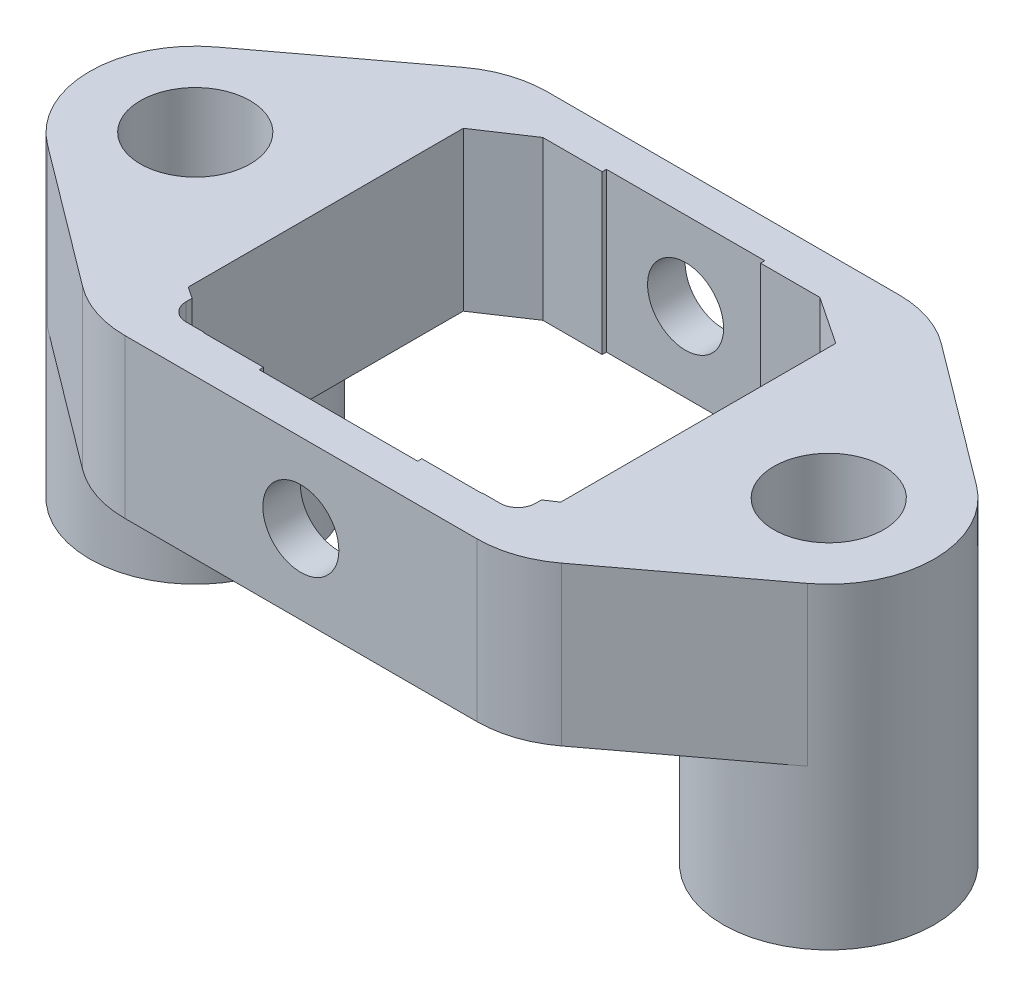
SolidWorks part; units mm, degrees
ref_plane "Front Plane" through (0, 0, 0) normal (0, 0, 1) x (1, 0, 0)
ref_plane "Top Plane" through (0, 0, 0) normal (0, 1, 0) x (1, 0, 0)
ref_plane "Right Plane" through (0, 0, 0) normal (1, 0, 0) x (0, 0, -1)
sketch "Sketch1" plane through (0, 0, 0) normal (0, 1, 0) x (1, 0, 0)
  line L0 (4.7625, -10.1854) -> (8.3298, -10.1854)
  line L5 (-4.7625, 10.1854) -> (-4.7625, 10.4394)
  line L6 (-12.7, -12.7) -> (12.7, -12.7)
  line L7 (4.7625, 10.1854) -> (8.3298, 10.1854)
  line L8 (-8.3298, 10.1854) -> (-11.2014, 8.271)
  line L9 (-8, 10.1) -> (-11, 8.1) construction
  line L10 (0, 0) -> (-11.2014, 0) construction
  line L11 (0, 0) -> (0, 10.4394) construction
  line L12 (-8.3298, -10.1854) -> (-8.3769, -10.154)
  line L13 (8.3298, -10.1854) -> (8.3769, -10.154)
  line L14 (8.3298, 10.1854) -> (11.2014, 8.271)
  line L15 (-8.3298, 10.1854) -> (-4.7625, 10.1854)
  line L34 (-10.504, -8.7359) -> (-11.2014, -8.271)
  line L35 (8.3769, -10.154) -> (9.4165, -10.154)
  line L36 (9.5863, -10.1409) -> (9.6154, -10.1409)
  line L37 (-9.5863, -10.1409) -> (-9.6154, -10.1409)
  line L38 (-8.75, -10.154) -> (-9.4165, -10.154)
  line L39 (-10.504, -9.1) -> (-10.504, -8.9)
  line L40 (-9.5863, -10.1409) -> (-9.6154, -10.1409)
  line L41 (-8.3769, -10.154) -> (-9.4165, -10.154)
  line L42 (-10.504, -9.1) -> (-10.504, -8.7359)
  line L43 (10.504, -9.1) -> (10.504, -8.7359)
  line L44 (10.504, -8.7359) -> (11.2014, -8.271)
  line L45 (-12.7, 12.7) -> (-22.86, 5.08)
  line L46 (-22.86, -5.08) -> (-12.7, -12.7)
  line L47 (12.7, 12.7) -> (22.86, 5.08)
  line L48 (22.86, -5.08) -> (12.7, -12.7)
  line L284 (-12.7, 12.7) -> (12.7, 12.7)
  line L286 (-12.7, -12.7) -> (12.7, 12.7) construction
  line L287 (-12.7, 12.7) -> (12.7, -12.7) construction
  line L288 (-8.3298, -10.1854) -> (-4.7625, -10.1854)
  line L289 (-11.2014, -8.271) -> (-11.2014, 8.271)
  line L291 (11.2014, -8.271) -> (11.2014, 8.271)
  line L326 (-4.7625, 10.4394) -> (4.7625, 10.4394)
  line L327 (4.7625, 10.4394) -> (4.7625, 10.1854)
  line L328 (-4.7625, -10.1854) -> (-4.7625, -10.4394)
  line L335 (-4.7625, -10.4394) -> (4.7625, -10.4394)
  line L338 (4.7625, -10.4394) -> (4.7625, -10.1854)
  arc A7 (9.5863, -10.1409) -> (9.4165, -10.154) centre (9.4168, -9.0458) cw
  arc A8 (-9.5863, -10.1409) -> (-9.4165, -10.154) centre (-9.4168, -9.0458) ccw
  arc A9 (-10.504, -9.1) -> (-9.6154, -10.1409) centre (-9.45, -9.1) ccw
  arc A10 (-9.5863, -10.1409) -> (-9.4165, -10.154) centre (-9.4168, -9.0458) ccw
  arc A11 (-10.504, -9.1) -> (-9.6154, -10.1409) centre (-9.45, -9.1) ccw
  arc A12 (10.504, -9.1) -> (9.6154, -10.1409) centre (9.45, -9.1) cw
  circle A13 centre (-19.05, 0) radius 3.302
  circle A14 centre (19.05, 0) radius 3.302
  arc A15 (-22.86, 5.08) -> (-22.86, -5.08) centre (-19.05, 0) ccw
  arc A16 (22.86, 5.08) -> (22.86, -5.08) centre (19.05, 0) cw
  point P0 (0, 0)
  point P6 (0, 0)
  point P15 (0, 10.4394)
  point P23 (0, -10.4394)
  point P38 (0, 0)
  point P48 (-4.7625, -11.2687)
  dimension "D4" = 6.604
  dimension "D10" = 6.604
  dimension "D13" = 6.35
  dimension "D14" = 6.35
  dimension "D1" = 25.4
  dimension "D2" = 25.4
  dimension "D3" = 0.254
  dimension "D5" = 9.525
  dimension "D6" = 22.4028
  dimension "D7" = 0.254
  dimension "D8" = 20.3708
  dimension "D9" = 0.254
  dimension "D11" = 19.05
  dimension "D12" = 19.05
  dimension "D15" = 0.254
extrude "Boss-Extrude1" add sketch "Sketch1" along normal blind 9.525
fillet "Fillet1" radius 6.35 4 edges at (-12.7, 4.7625, 12.7) (12.7, 4.7625, 12.7) (-12.7, 4.7625, -12.7) (12.7, 4.7625, -12.7)
sketch "Sketch2" plane through (0, 0, 12.7) normal (0, 0, 1) x (1, 0, 0)
  circle A0 centre (0, 4.7625) radius 2.286
  point P2 (0, 0)
  dimension "D2" = 4.572
  dimension "D1" = 4.7625
extrude "Cut-Extrude1" cut sketch "Sketch2" against normal through all
sketch "Sketch3" plane through (0, 0, 0) normal (0, -1, 0) x (-1, 0, 0)
  circle A0 centre (19.05, 0) radius 6.35
  circle A1 centre (-19.05, 0) radius 6.35
  arc A2 (22.86, -5.08) -> (22.86, 5.08) centre (19.05, 0) ccw construction
  arc A3 (-22.86, 5.08) -> (-22.86, -5.08) centre (-19.05, 0) ccw construction
  circle A4 centre (19.05, 0) radius 3.302 construction
  circle A5 centre (-19.05, 0) radius 3.302 construction
  circle A6 centre (19.05, 0) radius 3.302
  circle A7 centre (-19.05, 0) radius 3.302
extrude "Boss-Extrude2" add sketch "Sketch3" along normal blind 9.525
